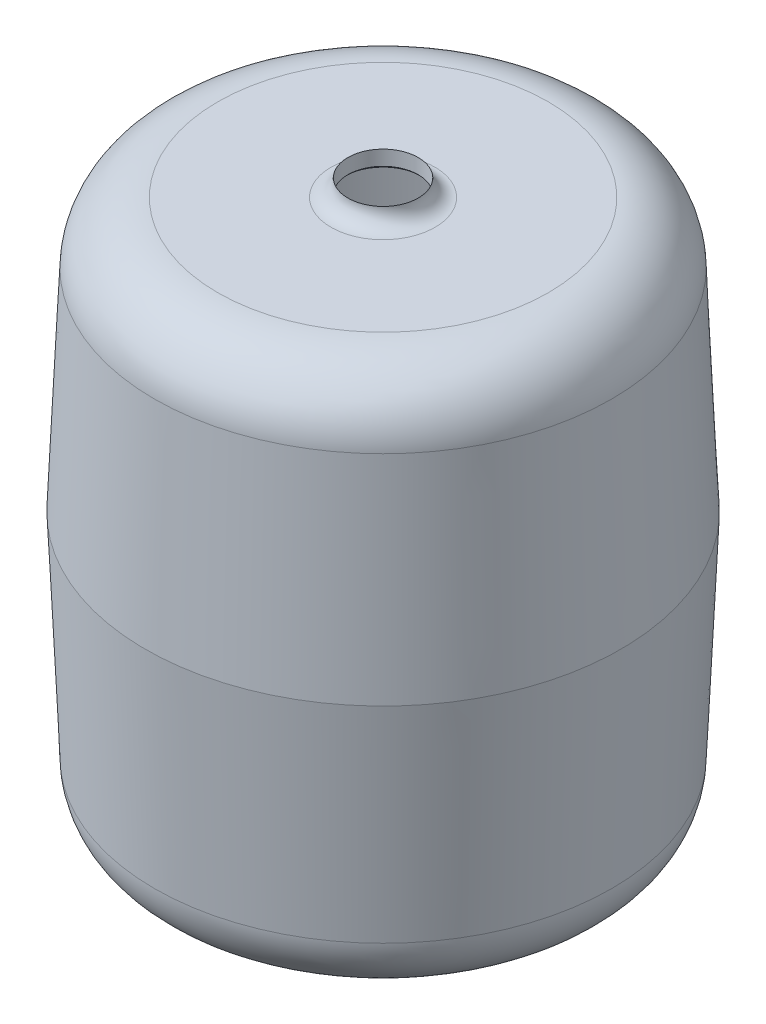
SolidWorks part; units mm, degrees
ref_plane "Front Plane" through (0, 0, 0) normal (0, 0, 1) x (1, 0, 0)
ref_plane "Top Plane" through (0, 0, 0) normal (0, 1, 0) x (1, 0, 0)
ref_plane "Right Plane" through (0, 0, 0) normal (1, 0, 0) x (0, 0, -1)
sketch "Sketch2" plane through (0, 0, 0) normal (0, 0, 1) x (1, 0, 0)
  line L0 (0, 0) -> (6.5803, 150.7129)
  line L1 (51.5374, 193.75) -> (132.0803, 193.75)
  line L2 (169.0803, 213.75) -> (144.0803, 213.75)
  line L3 (144.0803, 213.75) -> (144.0803, 205.75)
  line L4 (-219.3927, 0) -> (495.9295, 0) construction
  line L5 (169.0803, 332.4616) -> (169.0803, -231.1331) construction
  line L6 (0, 0) -> (6.5803, -150.7129)
  line L7 (51.5374, -193.75) -> (169.0803, -193.75)
  line L8 (165.0803, 209.75) -> (165.0803, -189.75)
  line L9 (165.0803, 209.75) -> (148.0803, 209.75)
  line L10 (148.0803, 209.75) -> (148.0803, 205.75)
  line L11 (51.5374, 189.75) -> (132.0803, 189.75)
  line L12 (4.0038, 0) -> (10.5765, 150.5384)
  line L13 (4.0038, 0) -> (10.5765, -150.5384)
  line L14 (51.5374, -189.75) -> (165.0803, -189.75)
  line L16 (165.0803, 209.75) -> (165.0803, -189.75) construction
  line L17 (169.0803, 213.75) -> (169.0803, -193.75) construction
  line L18 (169.0803, 213.75) -> (169.0803, -193.75)
  arc A0 (6.5803, 150.7129) -> (51.5374, 193.75) centre (51.5374, 148.75) cw
  arc A1 (132.0803, 193.75) -> (144.0803, 205.75) centre (132.0803, 205.75) ccw
  arc A2 (6.5803, -150.7129) -> (51.5374, -193.75) centre (51.5374, -148.75) ccw
  arc A3 (132.0803, 189.75) -> (148.0803, 205.75) centre (132.0803, 205.75) ccw
  arc A4 (10.5765, 150.5384) -> (51.5374, 189.75) centre (51.5374, 148.75) cw
  arc A5 (10.5765, -150.5384) -> (51.5374, -189.75) centre (51.5374, -148.75) ccw
  point P6 (8.4593, 193.75)
  dimension "D4" = 45
  dimension "D3" = 12
  dimension "D9" = 45
  dimension "D1" = 92.5
  dimension "D5" = 25
  dimension "D6" = 20
  dimension "D2" = 387.5
  dimension "D7" = 92.5
  dimension "D8" = 162.5
  dimension "D10" = 162.5
  dimension "D11" = 4
revolve "Revolve1" add sketch "Sketch2" angle 360 about L18
sketch "Sketch3" plane through (0, 213.75, 0) normal (0, 1, 0) x (1, 0, 0)
  circle A0 centre (169.0803, 0) radius 25
extrude "Cut-Extrude4" cut sketch "Sketch3" against normal blind 405.5
equation "\"A\"= 325mm"
equation "\"B\"= 387.5mm"
equation "\"D2@Sketch2\"=\"B\""
